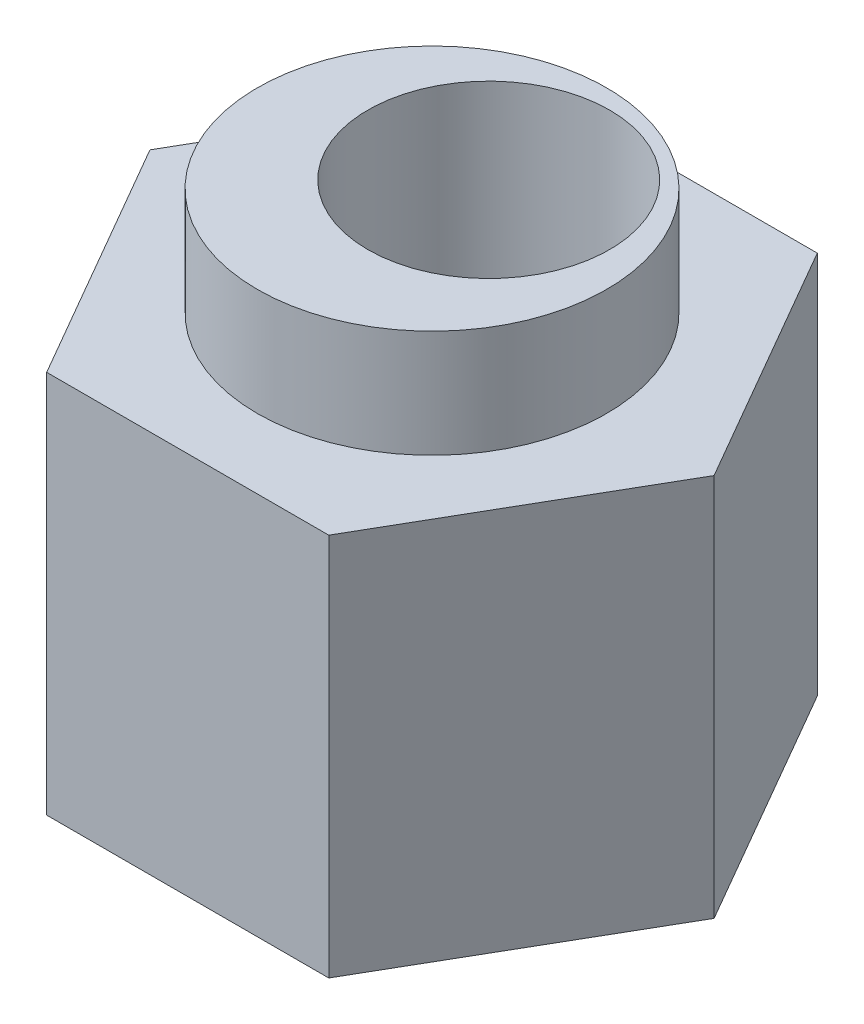
SolidWorks part; units mm, degrees
ref_plane "Front Plane" through (0, 0, 0) normal (0, 0, 1) x (1, 0, 0)
ref_plane "Top Plane" through (0, 0, 0) normal (0, 1, 0) x (1, 0, 0)
ref_plane "Right Plane" through (0, 0, 0) normal (1, 0, 0) x (0, 0, -1)
sketch "Sketch1" plane through (0, 0, 0) normal (0, 1, 0) x (1, 0, 0)
  line L1 (2.8868, 5) -> (-2.8868, 5)
  line L2 (-2.8868, 5) -> (-5.7735, 0)
  line L3 (-5.7735, 0) -> (-2.8868, -5)
  line L4 (-2.8868, -5) -> (2.8868, -5)
  line L5 (2.8868, -5) -> (5.7735, 0)
  line L6 (5.7735, 0) -> (2.8868, 5)
  circle A0 centre (0, 0) radius 5 construction
  dimension "D1" = 10
extrude "Boss-Extrude1" add sketch "Sketch1" along normal mid plane 7.85
sketch "Sketch2" plane through (0, 3.925, 0) normal (0, 1, 0) x (1, 0, 0)
  circle A0 centre (0, 0) radius 3.575
  dimension "D1" = 7.15
extrude "Boss-Extrude2" add sketch "Sketch2" along normal blind 2.2
sketch "Sketch3" plane through (0, 6.125, 0) normal (0, 1, 0) x (1, 0, 0)
  line L1 (2.8868, 5) -> (1.7875, 3.096) construction
  line L2 (1.7875, 3.096) -> (1.6625, 2.8795) construction
  line L3 (1.6625, 2.8795) -> (0, 0) construction
  circle A0 centre (0.425, 0.7361) radius 2.475
  circle A1 centre (0, 0) radius 3.575 construction
  dimension "D1" = 4.95
  dimension "D2" = 0.25
extrude "Cut-Extrude1" cut sketch "Sketch3" against normal through all
sketch "Sketch4" plane through (0, -3.925, 0) normal (0, -1, 0) x (1, 0, 0)
  circle A0 centre (0.425, -0.7361) radius 3.5
  circle A1 centre (0.425, -0.7361) radius 2.475 construction
  circle A2 centre (0.425, -0.7361) radius 2.475
  dimension "D1" = 7
extrude "Boss-Extrude3" add sketch "Sketch4" along normal blind 0.5
